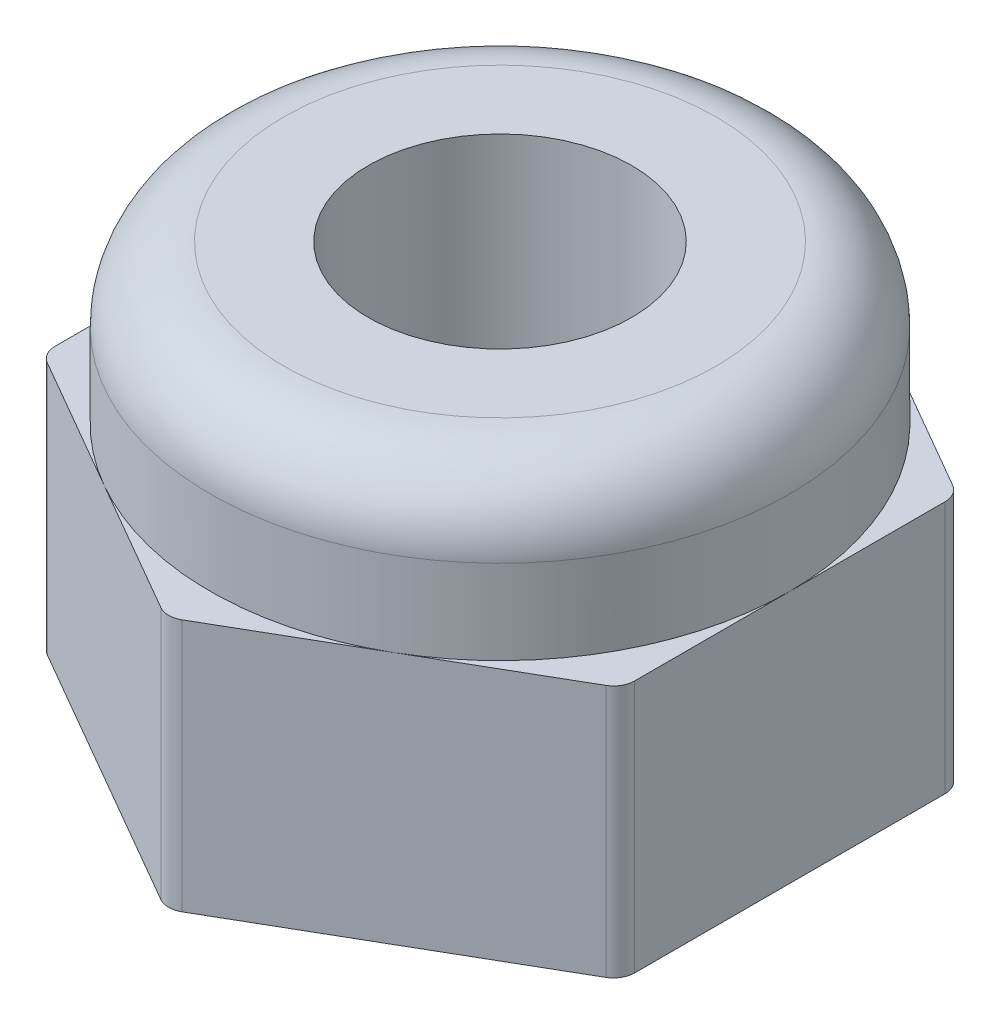
SolidWorks part; units mm, degrees
ref_plane "前视基准面" through (0, 0, 0) normal (0, 0, 1) x (1, 0, 0)
ref_plane "上视基准面" through (0, 0, 0) normal (0, 1, 0) x (1, 0, 0)
ref_plane "右视基准面" through (0, 0, 0) normal (1, 0, 0) x (0, 0, -1)
sketch "草图1" plane through (0, 0, 0) normal (0, 1, 0) x (1, 0, 0)
  line L1 (0, 3.1754) -> (-2.75, 1.5877)
  line L2 (-2.75, 1.5877) -> (-2.75, -1.5877)
  line L3 (-2.75, -1.5877) -> (0, -3.1754)
  line L4 (0, -3.1754) -> (2.75, -1.5877)
  line L5 (2.75, -1.5877) -> (2.75, 1.5877)
  line L6 (2.75, 1.5877) -> (0, 3.1754)
  circle A0 centre (0, 0) radius 2.75 construction
  dimension "D1" = 5.5
extrude "凸台-拉伸1" add sketch "草图1" along normal blind 2.4
sketch "草图2" plane through (0, 0, 0) normal (0, -1, 0) x (1, 0, 0)
  line L0 (2.75, 1.5877) -> (2.75, -1.5877) construction
  circle A0 centre (0, 0) radius 2.75
extrude "凸台-拉伸2" add sketch "草图2" against normal blind 3.9 contours A0
fillet "圆角1" radius 0.7 1 edges at (0, 3.9, -2.75)
fillet "圆角2" radius 0.2 6 edges at (-2.75, 1.2, 1.5877) (-2.75, 1.2, -1.5877) (0, 1.2, -3.1754) (2.75, 1.2, -1.5877) (2.75, 1.2, 1.5877) (0, 1.2, 3.1754)
hole_wizard "M3 螺纹孔1" positions "草图3" profile "草图4" tap size "M3" standard "ISO"
sketch "草图3" plane through (0, 0, 0) normal (0, -1, 0) x (-1, 0, 0)
  point P0 (0, 0)
sketch "草图4" plane through (0, 0, 0) normal (1, 0, 0) x (0, 0, -1)
  line L0 (0, 0) -> (0, 8.2511)
  line L1 (0, 8.2511) -> (1.25, 7.5)
  line L2 (1.25, 7.5) -> (1.25, 0)
  line L5 (1.25, 0) -> (0, 0)
  line L10 (0, 8.2511) -> (-1.25, 7.5) construction
  line L11 (0, -6.35) -> (0, 107.95) construction
  dimension "螺纹孔钻头直径" = 2.5
  dimension "螺纹孔钻头深度" = 7.5
  dimension "导头角度" = 118
cosmetic thread "孔螺蚊线1" parameters "D1"=6, "D2"=3
